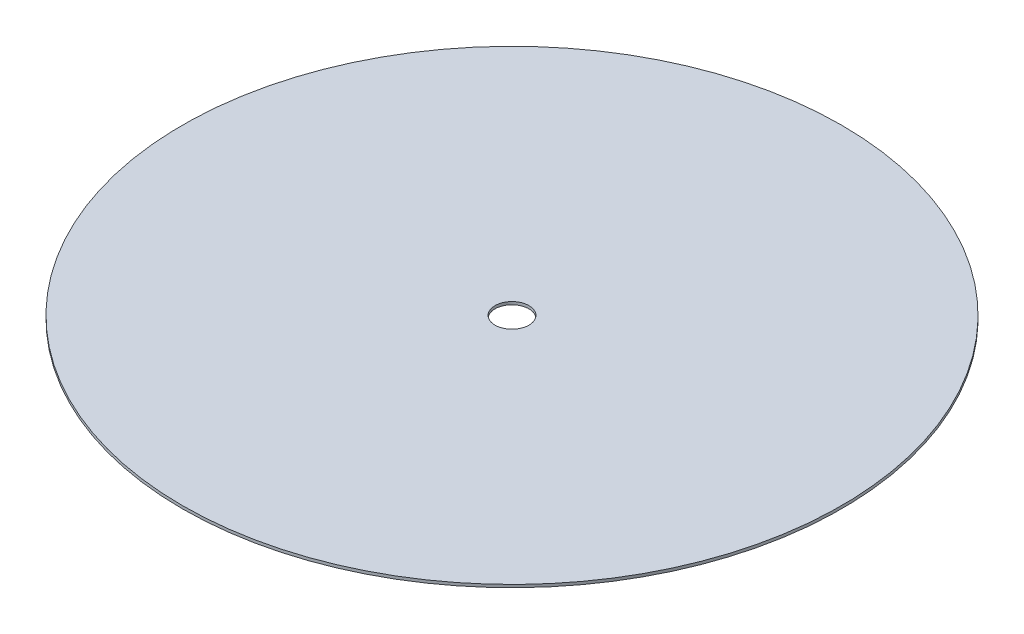
SolidWorks part; units mm, degrees
ref_plane "Front Plane" through (0, 0, 0) normal (0, 0, 1) x (1, 0, 0)
ref_plane "Top Plane" through (0, 0, 0) normal (0, 1, 0) x (1, 0, 0)
ref_plane "Right Plane" through (0, 0, 0) normal (1, 0, 0) x (0, 0, -1)
sketch "Sketch1" plane through (0, 0, 0) normal (0, 1, 0) x (1, 0, 0)
  circle A0 centre (0, 0) radius 1750
extrude "Boss-Extrude1" add sketch "Sketch1" along normal blind 15
sketch "Sketch2" plane through (0, 15, 0) normal (0, 1, 0) x (1, 0, 0)
  circle A1 centre (0, 0) radius 90
extrude "Cut-Extrude1" cut sketch "Sketch2" against normal blind 50
